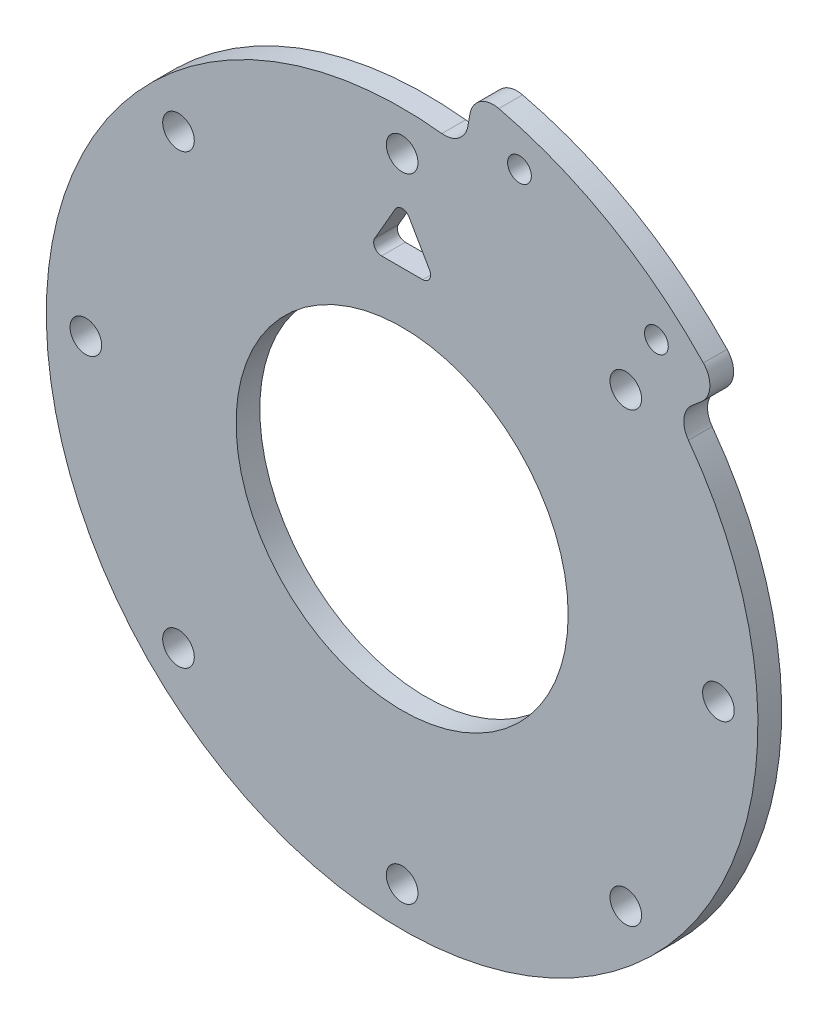
SolidWorks part; units mm, degrees
ref_plane "前视基准面" through (0, 0, 0) normal (0, 0, 1) x (1, 0, 0)
ref_plane "上视基准面" through (0, 0, 0) normal (0, 1, 0) x (1, 0, 0)
ref_plane "右视基准面" through (0, 0, 0) normal (1, 0, 0) x (0, 0, -1)
sketch "草图1" plane through (0, 0, 0) normal (0, 0, 1) x (1, 0, 0)
  circle A0 centre (0, 0) radius 21
  circle A2 centre (0, 0) radius 45
  dimension "D1" = 42
  dimension "D2" = 90
extrude "凸台-拉伸1" add sketch "草图1" along normal blind 3
sketch "草图2" plane through (0, 0, 3) normal (0, 0, 1) x (1, 0, 0)
  line L0 (0, 0) -> (0, 40) construction
  circle A0 centre (0, 40) radius 2
  circle A1 centre (28.2843, 28.2843) radius 2
  circle A2 centre (40, 0) radius 2
  circle A3 centre (28.2843, -28.2843) radius 2
  circle A4 centre (0, -40) radius 2
  circle A5 centre (-28.2843, -28.2843) radius 2
  circle A6 centre (-40, 0) radius 2
  circle A7 centre (-28.2843, 28.2843) radius 2
  point P21 (0, 0)
  dimension "D2" = 4
  dimension "D1" = 40
  dimension "D3" = 8
extrude "切除-拉伸1" cut sketch "草图2" against normal blind 10
sketch "草图3" plane through (0, 0, 3) normal (0, 0, 1) x (1, 0, 0)
  line L0 (0, 0) -> (49000.4852, 0) construction
  line L1 (-50.6998, -28.0183) -> (-50.6998, -23.5585) construction
  line L2 (0, 0) -> (25.4212, 44.0308) construction
  line L3 (14.8397, 45.7032) -> (32.1603, 35.7032) construction
  line L4 (7.8142, 44.3163) -> (9.1165, 51.7024)
  line L5 (34.472, 28.9254) -> (40.2173, 33.7463)
  circle A0 centre (32.1603, 35.7032) radius 1.5
  circle A1 centre (14.8397, 45.7032) radius 1.5
  arc A2 (40.2173, 33.7463) -> (9.1165, 51.7024) centre (0, 0) ccw
  circle A3 centre (0, 0) radius 45 construction
  arc A4 (34.472, 28.9254) -> (45, 0) centre (0, 0) ccw
  point P7 (23.5, 40.7032)
  circle M15 centre (0, 0) radius 45
  dimension "D4" = 3
  dimension "D5" = 3
  dimension "D6" = 105
  dimension "D1" = 60
  dimension "D2" = 20
  dimension "D3" = 47
  dimension "D7" = 20
sketch "草图4" plane through (0, 0, 3) normal (0, 0, 1) x (1, 0, 0)
  line L1 (4.3301, 27.5) -> (0, 35)
  line L2 (0, 35) -> (-4.3301, 27.5)
  line L3 (-4.3301, 27.5) -> (4.3301, 27.5)
  circle A0 centre (0, 30) radius 2.5 construction
  dimension "D1" = 5
  dimension "D2" = 30
extrude "切除-拉伸2" cut sketch "草图4" against normal blind 3
extrude "凸台-拉伸3" add sketch "草图3" against normal blind 3 contours L5 A2 L4 M15
fillet "圆角2" radius 1 3 edges at (-4.3301, 27.5, 1.5) (4.3301, 27.5, 1.5) (0, 35, 1.5)
fillet "圆角3" radius 3 4 edges at (34.472, 28.9254, 1.5) (7.8142, 44.3163, 1.5) (9.1165, 51.7024, 1.5) (40.2173, 33.7463, 1.5)
